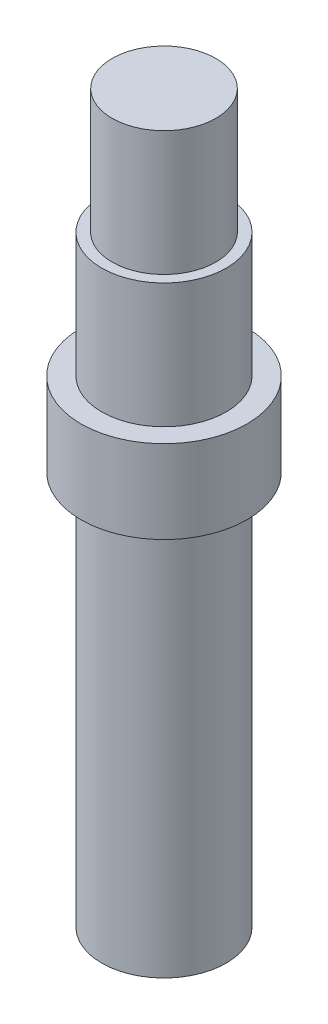
SolidWorks part; units mm, degrees
ref_plane "Front" through (0, 0, 0) normal (0, 0, 1) x (1, 0, 0)
ref_plane "Top" through (0, 0, 0) normal (0, 1, 0) x (1, 0, 0)
ref_plane "Right" through (0, 0, 0) normal (1, 0, 0) x (0, 0, -1)
sketch "草图1" plane through (0, 0, 0) normal (0, 1, 0) x (1, 0, 0)
  circle A0 centre (0, 0) radius 6
  dimension "D1" = 12
extrude "凸台-拉伸1" add sketch "草图1" along normal blind 38
sketch "草图2" plane through (0, 38, 0) normal (0, 1, 0) x (1, 0, 0)
  circle A0 centre (0, 0) radius 8
  dimension "D1" = 16
extrude "凸台-拉伸2" add sketch "草图2" along normal blind 8
sketch "草图3" plane through (0, 46, 0) normal (0, 1, 0) x (1, 0, 0)
  circle A0 centre (0, 0) radius 6
  dimension "D1" = 12
sketch "草图4" plane through (0, 46, 0) normal (0, 1, 0) x (1, 0, 0)
  circle A0 centre (0, 0) radius 6
  dimension "D1" = 12
extrude "凸台-拉伸3" add sketch "草图4" along normal blind 12
sketch "草图5" plane through (0, 58, 0) normal (0, 1, 0) x (1, 0, 0)
  circle A0 centre (0, 0) radius 5
  dimension "D1" = 10
extrude "凸台-拉伸4" add sketch "草图5" along normal blind 12
